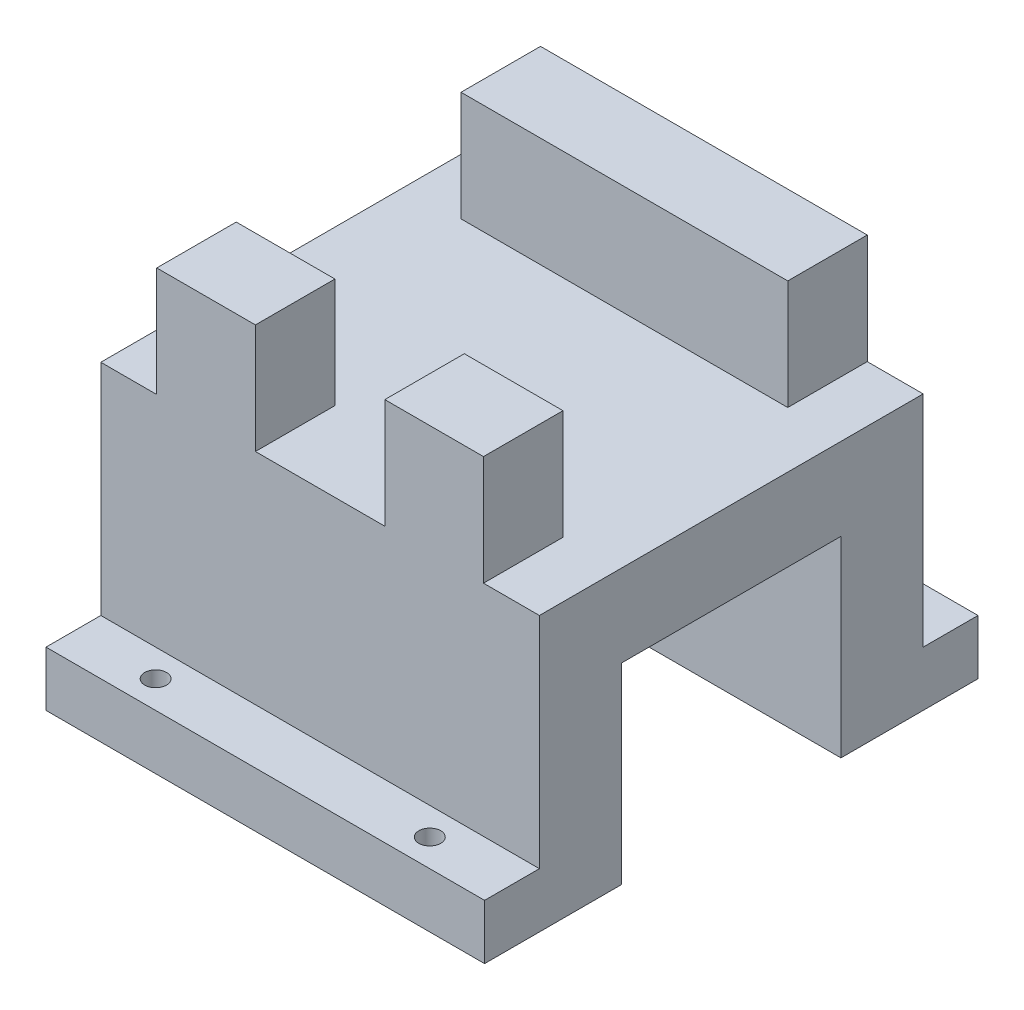
SolidWorks part; units mm, degrees
ref_plane "Front Plane" through (0, 0, 0) normal (0, 0, 1) x (1, 0, 0)
ref_plane "Top Plane" through (0, 0, 0) normal (0, 1, 0) x (1, 0, 0)
ref_plane "Right Plane" through (0, 0, 0) normal (1, 0, 0) x (0, 0, -1)
sketch "Sketch1" plane through (0, 0, 0) normal (0, 1, 0) x (1, 0, 0)
  line L1 (40, 45) -> (-40, 45)
  line L2 (40, 45) -> (40, -45)
  line L3 (40, -45) -> (-40, -45)
  line L4 (-40, 45) -> (-40, -45)
  line L5 (40, 45) -> (-40, -45) construction
  line L6 (40, -45) -> (-40, 45) construction
  point P0 (0, 0)
extrude "Boss-Extrude1" add sketch "Sketch1" along normal blind 10
sketch "Sketch2" plane through (0, 10, 0) normal (0, 1, 0) x (1, 0, 0)
  line L0 (-40, 45) -> (-40, -45) construction
  line L1 (40, 35) -> (-40, 35)
  line L2 (40, 35) -> (40, -35)
  line L3 (40, -35) -> (-40, -35)
  line L4 (-40, 35) -> (-40, -35)
  line L5 (40, 35) -> (-40, -35) construction
  line L6 (40, -35) -> (-40, 35) construction
  point P0 (0, 0)
extrude "Boss-Extrude2" add sketch "Sketch2" along normal blind 40
sketch "Sketch3" plane through (0, 50, 0) normal (0, 1, 0) x (1, 0, 0)
  line L0 (-40, -35) -> (40, -35) construction
  line L1 (-29.8, -35) -> (29.8, -35)
  line L2 (-29.8, -35) -> (-29.8, -20.5)
  line L3 (-29.8, -20.5) -> (29.8, -20.5)
  line L4 (29.8, -35) -> (29.8, -20.5)
  line L5 (40, 35) -> (-40, 35) construction
  line L6 (-29.8, 35) -> (29.8, 35)
  line L7 (-29.8, 35) -> (-29.8, 20.5)
  line L8 (-29.8, 20.5) -> (29.8, 20.5)
  line L9 (29.8, 35) -> (29.8, 20.5)
  line L10 (-40, 35) -> (-40, -35) construction
  line L11 (40, -35) -> (40, 35) construction
  point P14 (-29.8, -27.75)
  dimension "D1" = 10.2
  dimension "D2" = 10.2
  dimension "D3" = 41
  dimension "D4" = 10.2
  dimension "D5" = 10.2
extrude "Boss-Extrude3" add sketch "Sketch3" along normal blind 20
sketch "Sketch6" plane through (0, 0, 35) normal (0, 0, 1) x (1, 0, 0)
  line L0 (-29.8, 70) -> (29.8, 70) construction
  line L1 (-11.8, 70) -> (11.8, 70)
  line L2 (-11.8, 70) -> (-11.8, 50)
  line L3 (-11.8, 50) -> (11.8, 50)
  line L4 (11.8, 70) -> (11.8, 50)
  line L5 (-29.8, 70) -> (-29.8, 50) construction
  line L6 (29.8, 70) -> (29.8, 50) construction
  dimension "D1" = 20
  dimension "D2" = 18
  dimension "D3" = 18
extrude "Cut-Extrude1" cut sketch "Sketch6" against normal up to next
sketch "Sketch7" plane through (-40, 0, 0) normal (-1, 0, 0) x (0, 0, 1)
  line L0 (-45, 0) -> (45, 0) construction
  line L1 (-20, 0) -> (20, 0)
  line L2 (-20, 0) -> (-20, 35)
  line L3 (-20, 35) -> (20, 35)
  line L4 (20, 0) -> (20, 35)
  line L5 (-35, 50) -> (-35, 10) construction
  line L6 (35, 50) -> (35, 10) construction
  dimension "D1" = 15
  dimension "D2" = 15
  dimension "D3" = 35
extrude "Cut-Extrude2" cut sketch "Sketch7" against normal up to next
sketch "Sketch8" plane through (0, 10, 0) normal (0, 1, 0) x (1, 0, 0)
  line L0 (-40, -35) -> (-40, -45) construction
  line L3 (-40, -45) -> (40, -45) construction
  line L4 (40, -45) -> (40, -35) construction
  line L5 (40, 35) -> (40, 45) construction
  line L6 (40, 45) -> (-40, 45) construction
  line L7 (-40, 45) -> (-40, 35) construction
  circle A0 centre (-25, -40) radius 2
  circle A1 centre (25, -40) radius 2
  circle A2 centre (25, 40) radius 2
  circle A3 centre (-25, 40) radius 2
  dimension "D1" = 15
  dimension "D2" = 5
  dimension "D3" = 15
  dimension "D4" = 5
  dimension "D5" = 15
  dimension "D6" = 5
  dimension "D7" = 15
  dimension "D8" = 5
extrude "Cut-Extrude3" cut sketch "Sketch8" against normal up to next
